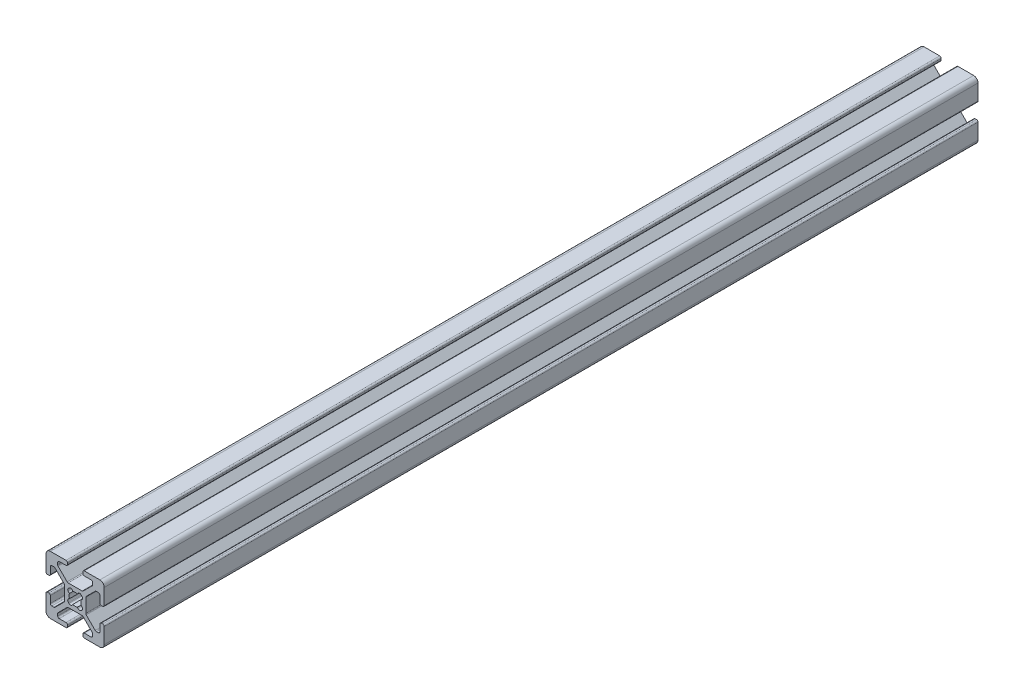
SolidWorks part; units mm, degrees
ref_plane "Front Plane" through (0, 0, 0) normal (0, 0, 1) x (1, 0, 0)
ref_plane "Top Plane" through (0, 0, 0) normal (0, 1, 0) x (1, 0, 0)
ref_plane "Right Plane" through (0, 0, 0) normal (1, 0, 0) x (0, 0, -1)
ref_plane "Plane1" through (0, 0, 4000) normal (0, 0, 1) x (1, 0, 0)
sketch "Sketch1" plane through (0, 0, 4000) normal (0, 0, 1) x (1, 0, 0)
  line B0 (10, 3.138) -> (10, 8.5)
  line B1 (8.5, 10) -> (3.138, 10)
  line B2 (2.63, 9.492) -> (2.63, 9.008)
  line B3 (3.138, 8.5) -> (5.487, 8.5)
  line B4 (5.995, 7.992) -> (5.995, 7.2661)
  line B5 (5.8462, 6.9069) -> (2.7431, 3.8038)
  line B6 (2.3839, 3.655) -> (-2.3839, 3.655)
  line B7 (-2.7431, 3.8038) -> (-5.8462, 6.9069)
  line B8 (-5.995, 7.2661) -> (-5.995, 7.992)
  line B9 (-5.487, 8.5) -> (-3.138, 8.5)
  line B10 (-2.63, 9.008) -> (-2.63, 9.492)
  line B11 (-3.138, 10) -> (-8.5, 10)
  line B12 (-10, 8.5) -> (-10, 3.138)
  line B13 (-9.492, 2.63) -> (-9.008, 2.63)
  line B14 (-8.5, 3.138) -> (-8.5, 5.487)
  line B15 (-7.992, 5.995) -> (-7.2661, 5.995)
  line B16 (-6.9069, 5.8462) -> (-3.8038, 2.7431)
  line B17 (-3.655, 2.3839) -> (-3.655, -2.3839)
  line B18 (-3.8038, -2.7431) -> (-6.9069, -5.8462)
  line B19 (-7.2661, -5.995) -> (-7.992, -5.995)
  line B20 (-8.5, -5.487) -> (-8.5, -3.138)
  line B21 (-9.008, -2.63) -> (-9.492, -2.63)
  line B22 (-10, -3.138) -> (-10, -8.5)
  line B23 (-8.5, -10) -> (-3.138, -10)
  line B24 (-2.63, -9.492) -> (-2.63, -9.008)
  line B25 (-3.138, -8.5) -> (-5.487, -8.5)
  line B26 (-5.995, -7.992) -> (-5.995, -7.2661)
  line B27 (-5.8462, -6.9069) -> (-2.7431, -3.8038)
  line B28 (-2.3839, -3.655) -> (2.3839, -3.655)
  line B29 (2.7431, -3.8038) -> (5.8462, -6.9069)
  line B30 (5.995, -7.2661) -> (5.995, -7.992)
  line B31 (5.487, -8.5) -> (3.138, -8.5)
  line B32 (2.63, -9.008) -> (2.63, -9.492)
  line B33 (3.138, -10) -> (8.5, -10)
  line B34 (10, -8.5) -> (10, -3.138)
  line B35 (9.492, -2.63) -> (9.008, -2.63)
  line B36 (8.5, -3.138) -> (8.5, -5.487)
  line B37 (7.992, -5.995) -> (7.2661, -5.995)
  line B38 (6.9069, -5.8462) -> (3.8038, -2.7431)
  line B39 (3.655, -2.3839) -> (3.655, 2.3839)
  line B40 (3.8038, 2.7431) -> (6.9069, 5.8462)
  line B41 (7.2661, 5.995) -> (7.992, 5.995)
  line B42 (8.5, 5.487) -> (8.5, 3.138)
  line B43 (9.008, 2.63) -> (9.492, 2.63)
  line B44 (-2.1249, -2.3045) -> (-2.3045, -2.1249)
  line B45 (-2.3045, 2.1249) -> (-2.1249, 2.3045)
  line B46 (2.1249, 2.3045) -> (2.3045, 2.1249)
  line B47 (2.3045, -2.1249) -> (2.1249, -2.3045)
  arc B48 (9.492, 2.63) -> (10, 3.138) centre (9.492, 3.138) ccw
  arc B49 (10, 8.5) -> (8.5, 10) centre (8.5, 8.5) ccw
  arc B50 (3.138, 10) -> (2.63, 9.492) centre (3.138, 9.492) ccw
  arc B51 (2.63, 9.008) -> (3.138, 8.5) centre (3.138, 9.008) ccw
  arc B52 (5.487, 8.5) -> (5.995, 7.992) centre (5.487, 7.992) cw
  arc B53 (5.995, 7.2661) -> (5.8462, 6.9069) centre (5.487, 7.2661) cw
  arc B54 (2.7431, 3.8038) -> (2.3839, 3.655) centre (2.3839, 4.163) cw
  arc B55 (-2.3839, 3.655) -> (-2.7431, 3.8038) centre (-2.3839, 4.163) cw
  arc B56 (-5.8462, 6.9069) -> (-5.995, 7.2661) centre (-5.487, 7.2661) cw
  arc B57 (-5.995, 7.992) -> (-5.487, 8.5) centre (-5.487, 7.992) cw
  arc B58 (-3.138, 8.5) -> (-2.63, 9.008) centre (-3.138, 9.008) ccw
  arc B59 (-2.63, 9.492) -> (-3.138, 10) centre (-3.138, 9.492) ccw
  arc B60 (-8.5, 10) -> (-10, 8.5) centre (-8.5, 8.5) ccw
  arc B61 (-10, 3.138) -> (-9.492, 2.63) centre (-9.492, 3.138) ccw
  arc B62 (-9.008, 2.63) -> (-8.5, 3.138) centre (-9.008, 3.138) ccw
  arc B63 (-8.5, 5.487) -> (-7.992, 5.995) centre (-7.992, 5.487) cw
  arc B64 (-7.2661, 5.995) -> (-6.9069, 5.8462) centre (-7.2661, 5.487) cw
  arc B65 (-3.8038, 2.7431) -> (-3.655, 2.3839) centre (-4.163, 2.3839) cw
  arc B66 (-3.655, -2.3839) -> (-3.8038, -2.7431) centre (-4.163, -2.3839) cw
  arc B67 (-6.9069, -5.8462) -> (-7.2661, -5.995) centre (-7.2661, -5.487) cw
  arc B68 (-7.992, -5.995) -> (-8.5, -5.487) centre (-7.992, -5.487) cw
  arc B69 (-8.5, -3.138) -> (-9.008, -2.63) centre (-9.008, -3.138) ccw
  arc B70 (-9.492, -2.63) -> (-10, -3.138) centre (-9.492, -3.138) ccw
  arc B71 (-10, -8.5) -> (-8.5, -10) centre (-8.5, -8.5) ccw
  arc B72 (-3.138, -10) -> (-2.63, -9.492) centre (-3.138, -9.492) ccw
  arc B73 (-2.63, -9.008) -> (-3.138, -8.5) centre (-3.138, -9.008) ccw
  arc B74 (-5.487, -8.5) -> (-5.995, -7.992) centre (-5.487, -7.992) cw
  arc B75 (-5.995, -7.2661) -> (-5.8462, -6.9069) centre (-5.487, -7.2661) cw
  arc B76 (-2.7431, -3.8038) -> (-2.3839, -3.655) centre (-2.3839, -4.163) cw
  arc B77 (2.3839, -3.655) -> (2.7431, -3.8038) centre (2.3839, -4.163) cw
  arc B78 (5.8462, -6.9069) -> (5.995, -7.2661) centre (5.487, -7.2661) cw
  arc B79 (5.995, -7.992) -> (5.487, -8.5) centre (5.487, -7.992) cw
  arc B80 (3.138, -8.5) -> (2.63, -9.008) centre (3.138, -9.008) ccw
  arc B81 (2.63, -9.492) -> (3.138, -10) centre (3.138, -9.492) ccw
  arc B82 (8.5, -10) -> (10, -8.5) centre (8.5, -8.5) ccw
  arc B83 (10, -3.138) -> (9.492, -2.63) centre (9.492, -3.138) ccw
  arc B84 (9.008, -2.63) -> (8.5, -3.138) centre (9.008, -3.138) ccw
  arc B85 (8.5, -5.487) -> (7.992, -5.995) centre (7.992, -5.487) cw
  arc B86 (7.2661, -5.995) -> (6.9069, -5.8462) centre (7.2661, -5.487) cw
  arc B87 (3.8038, -2.7431) -> (3.655, -2.3839) centre (4.163, -2.3839) cw
  arc B88 (3.655, 2.3839) -> (3.8038, 2.7431) centre (4.163, 2.3839) cw
  arc B89 (6.9069, 5.8462) -> (7.2661, 5.995) centre (7.2661, 5.487) cw
  arc B90 (7.992, 5.995) -> (8.5, 5.487) centre (7.992, 5.487) cw
  arc B91 (8.5, 3.138) -> (9.008, 2.63) centre (9.008, 3.138) ccw
  arc B92 (0.804, -1.9351) -> (-0.804, -1.9351) centre (0, 0) cw
  arc B93 (-0.804, -1.9351) -> (-2.1249, -2.3045) centre (-1.5684, -1.748) cw
  arc B94 (-2.3045, -2.1249) -> (-1.9351, -0.804) centre (-1.748, -1.5684) cw
  arc B95 (-1.9351, -0.804) -> (-1.9351, 0.804) centre (0, 0) cw
  arc B96 (-1.9351, 0.804) -> (-2.3045, 2.1249) centre (-1.748, 1.5684) cw
  arc B97 (-2.1249, 2.3045) -> (-0.804, 1.9351) centre (-1.5684, 1.748) cw
  arc B98 (-0.804, 1.9351) -> (0.804, 1.9351) centre (0, 0) cw
  arc B99 (0.804, 1.9351) -> (2.1249, 2.3045) centre (1.5684, 1.748) cw
  arc B100 (2.3045, 2.1249) -> (1.9351, 0.804) centre (1.748, 1.5684) cw
  arc B101 (1.9351, 0.804) -> (1.9351, -0.804) centre (0, 0) cw
  arc B102 (1.9351, -0.804) -> (2.3045, -2.1249) centre (1.748, -1.5684) cw
  arc B103 (2.1249, -2.3045) -> (0.804, -1.9351) centre (1.5684, -1.748) cw
sketch_block_instance "Block1-1"
sketch_block "Block1"
extrude "Boss-Extrude1" add sketch "Sketch1" against normal blind 300
ref_plane "Płaszczyzna1" through (0, 0, 0) normal (-1, 0, 0) x (0, 0, 1)
